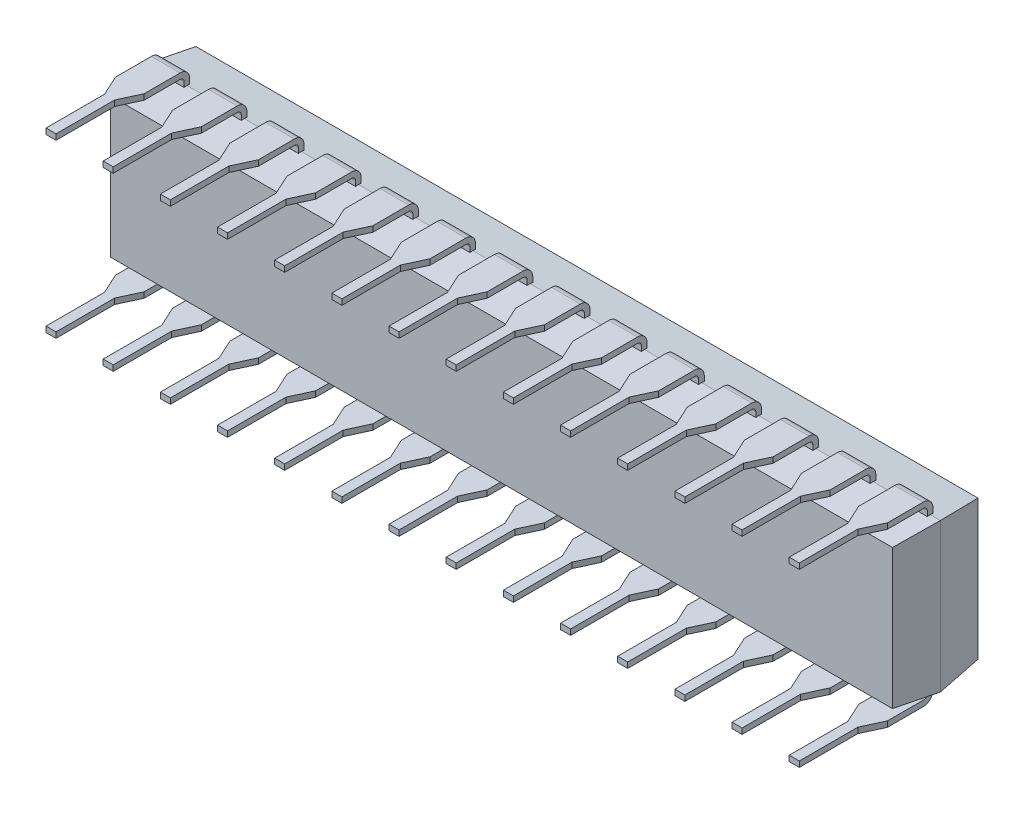
SolidWorks part; units mm, degrees
ref_plane "Plano frontal" through (0, 0, 0) normal (0, 0, 1) x (1, 0, 0)
ref_plane "Plano superior" through (0, 0, 0) normal (0, 1, 0) x (1, 0, 0)
ref_plane "Plano direito" through (0, 0, 0) normal (1, 0, 0) x (0, 0, -1)
sketch "Esboço1" plane through (0, 0, 0) normal (1, 0, 0) x (0, 0, -1)
  line L0 (0.9, 3.1) -> (0.9, -3.1)
  line L1 (0.9, -3.1) -> (2.8, -3.3)
  line L2 (2.8, -3.3) -> (4.7, -3.1)
  line L3 (4.7, -3.1) -> (4.7, 3.1)
  line L4 (4.7, 3.1) -> (2.8, 3.3)
  line L5 (2.8, 3.3) -> (0.9, 3.1)
  line L6 (2.8, 3.3) -> (2.8, -3.3) construction
  line L7 (4.7, 0) -> (2.8, 0) construction
  line L8 (2.8, 0) -> (0.9, 0) construction
  line L9 (0.9, 0) -> (0, 0) construction
  dimension "D1" = 6.6
  dimension "D2" = 6.2
  dimension "D3" = 3.8
  dimension "D4" = 0.9
extrude "Ressalto-extrusão1" add sketch "Esboço1" along normal mid plane 35.2
sketch "Esboço3" plane through (0, 0, 0) normal (0, 1, 0) x (1, 0, 0)
  line L0 (-17.6, 2.8) -> (-17.3699, 4.7268)
  line L1 (-17.3699, 4.7268) -> (-18.5363, 4.7268)
  line L2 (-18.5363, 4.7268) -> (-18.5363, 0.8732)
  line L3 (-18.5363, 0.8732) -> (-17.3699, 0.8732)
  line L4 (-17.3699, 0.8732) -> (-17.6, 2.8)
  line L5 (-18.5363, 2.8) -> (-17.6, 2.8) construction
  line L6 (-17.6, 0.9) -> (-17.6, 2.8) construction
  dimension "D1" = 6.81
  dimension "D2" = 3.8537
  dimension "D3" = 1.1665
extrude "Corte-extrusão2" cut sketch "Esboço3" against normal mid plane 7.1
mirror "Espelhar1" about plane through (0, 0, 0) normal (1, 0, 0) of "Corte-extrusão2"
sketch "Esboço8" plane through (0, 0, -4.7) normal (0, 0, -1) x (-1, 0, 0)
  line L0 (17.3731, -3.1) -> (17.3731, 3.1) construction
  circle A0 centre (17.3731, 0) radius 1
  dimension "D1" = 2
extrude "Corte-extrusão5" cut sketch "Esboço8" against normal blind 0.5
ref_plane "Plano1" through (0, 3.3, 0) normal (0, 1, 0) x (1, 0, 0)
sketch "Esboço6" plane through (0, 3.3, 0) normal (0, 1, 0) x (1, 0, 0)
  line L0 (-15.8725, 2.8) -> (0, 2.8) construction
  line L1 (-17.1475, 2.925) -> (-15.8725, 2.925)
  line L2 (-17.1475, 2.925) -> (-17.1475, 2.675)
  line L3 (-17.1475, 2.675) -> (-15.8725, 2.675)
  line L4 (-15.8725, 2.925) -> (-15.8725, 2.675)
  line L5 (17.6, 2.8) -> (-17.6, 2.8) construction
  line L6 (-16.51, 2.925) -> (-16.51, 2.675) construction
  dimension "D1" = 0.25
  dimension "D2" = 1.275
  dimension "D3" = 1.09
extrude "Ressalto-extrusão2" add sketch "Esboço6" along normal mid plane 0.05
sketch "Esboço7" plane through (0, 3.325, 0) normal (0, 1, 0) x (1, 0, 0)
  line L0 (-17.1475, 2.925) -> (-17.1475, 2.675) construction
  line L1 (-15.8725, 2.925) -> (-17.1475, 2.925) construction
  line L2 (-15.8725, 2.675) -> (-15.8725, 2.925) construction
  line L3 (-17.1475, 2.675) -> (-15.8725, 2.675) construction
  line L4 (-17.1475, 2.925) -> (-17.1475, 2.675)
  line L5 (-15.8725, 2.925) -> (-17.1475, 2.925)
  line L6 (-15.8725, 2.675) -> (-15.8725, 2.925)
  line L7 (-17.1475, 2.675) -> (-15.8725, 2.675)
  line L8 (-17.1475, 2.8) -> (-15.8725, 2.8) construction
sketch3d "3DSketch1"
  line L0 (-16.51, 3.325, -2.8) -> (-16.51, 3.51, -2.8)
  line L1 (-16.51, 3.325, -2.8) -> (-16.51, 0, -2.8) construction
  line L2 (-17.1475, 3.325, -2.8) -> (-15.8725, 3.325, -2.8) construction
  line L3 (-16.51, 3.81, -2.5) -> (-16.51, 3.81, 0)
  line L4 (-16.51, 0, -2.8) -> (0, 0, 0) construction
  arc A0 (-16.51, 3.51, -2.8) -> (-16.51, 3.81, -2.5) centre (-16.51, 3.51, -2.5) ccw
  point P5 (-16.21, 3.51, -2.5)
  dimension "D3" = 0.3
  dimension "D1" = 2.8
  dimension "D2" = 3.81
sweep "Varredura1" add profiles "Esboço7" path "3DSketch1"
sketch "Esboço9" plane through (0, 3.935, 0) normal (0, 1, 0) x (1, 0, 0)
  line L0 (-16.7325, 0) -> (-17.1475, 0.9)
  line L1 (-15.8725, 0) -> (-17.1475, 0) construction
  line L3 (-17.1475, 2.5) -> (-17.1475, 0) construction
  line L4 (-17.1475, 0.9) -> (-17.1475, -0.2)
  line L5 (-17.1475, -0.2) -> (-15.8725, -0.2)
  line L6 (-15.8725, -0.2) -> (-15.8725, 0.9)
  line L7 (-15.8725, 2.5) -> (-15.8725, 0) construction
  line L8 (-15.8725, 0.9) -> (-16.2875, 0)
  line L9 (-16.2875, 0) -> (-16.7325, 0)
  line L10 (-16.51, 0) -> (-16.51, 2.5) construction
  line L11 (-15.8725, 2.5) -> (-17.1475, 2.5) construction
  dimension "D1" = 0.9
  dimension "D2" = 0.445
  dimension "D3" = 0.2
extrude "Corte-extrusão6" cut sketch "Esboço9" against normal up to next
sketch "Esboço10" plane through (0, 0, 0) normal (0, 0, 1) x (1, 0, 0)
  line L0 (-16.2875, 3.935) -> (-16.7325, 3.935) construction
  line L1 (-16.7325, 3.935) -> (-16.7325, 3.685) construction
  line L2 (-16.7325, 3.685) -> (-16.2875, 3.685) construction
  line L3 (-16.2875, 3.685) -> (-16.2875, 3.935) construction
  line L4 (-16.2875, 3.935) -> (-16.7325, 3.935)
  line L5 (-16.7325, 3.935) -> (-16.7325, 3.685)
  line L6 (-16.7325, 3.685) -> (-16.2875, 3.685)
  line L7 (-16.2875, 3.685) -> (-16.2875, 3.935)
extrude "Ressalto-extrusão3" add sketch "Esboço10" along normal blind 2.6
mirror "Espelhar2" about plane through (0, 0, 0) normal (0, 1, 0) of "Ressalto-extrusão3", "Corte-extrusão6", "Varredura1", "Ressalto-extrusão2"
pattern_linear "Padrão linear1" count 14 spacing 2.54 along (1, 0, 0) of "Ressalto-extrusão2", "Varredura1", "Corte-extrusão6", "Ressalto-extrusão3", "Espelhar2"
